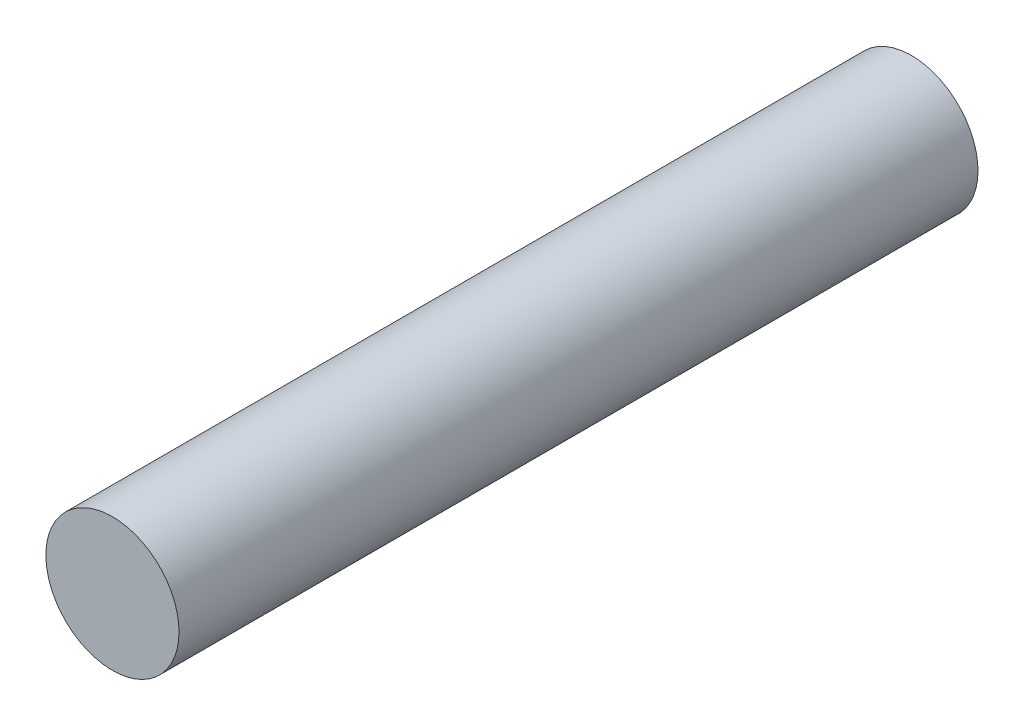
SolidWorks part; units mm, degrees
ref_plane "Front Plane" through (0, 0, 0) normal (0, 0, 1) x (1, 0, 0)
ref_plane "Top Plane" through (0, 0, 0) normal (0, 1, 0) x (1, 0, 0)
ref_plane "Right Plane" through (0, 0, 0) normal (1, 0, 0) x (0, 0, -1)
sketch "Sketch1" plane through (0, 0, 0) normal (0, 0, 1) x (1, 0, 0)
  circle A0 centre (0, 0) radius 0.125
  dimension "D1" = 0.25
extrude "Boss-Extrude1" add sketch "Sketch1" along normal blind 1.5
